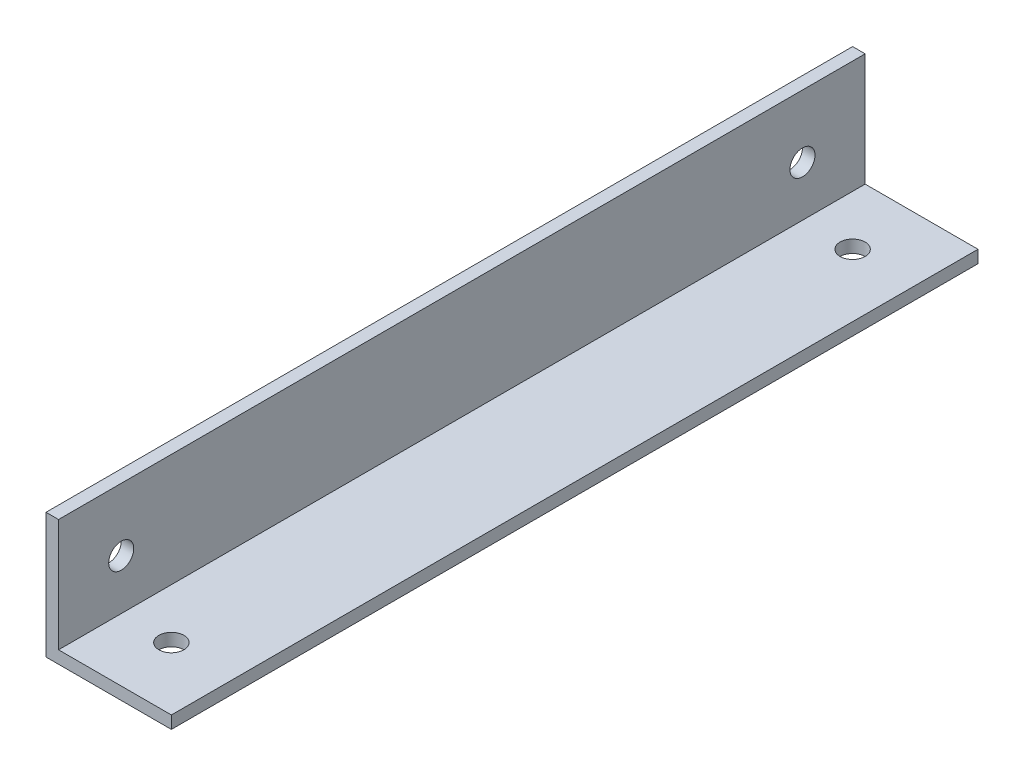
SolidWorks part; units mm, degrees
ref_plane "Plan de face" through (0, 0, 0) normal (0, 0, 1) x (1, 0, 0)
ref_plane "Plan de dessus" through (0, 0, 0) normal (0, 1, 0) x (1, 0, 0)
ref_plane "Plan de droite" through (0, 0, 0) normal (1, 0, 0) x (0, 0, -1)
sketch "Esquisse1" plane through (0, 0, 0) normal (0, 0, 1) x (1, 0, 0)
  line L0 (-19.573, -1.5638) -> (-19.573, -16.5638)
  line L1 (-19.573, -16.5638) -> (-4.573, -16.5638)
  line L2 (-4.573, -16.5638) -> (-4.573, -15.0638)
  line L3 (-4.573, -15.0638) -> (-18.073, -15.0638)
  line L4 (-18.073, -15.0638) -> (-18.073, -1.5638)
  line L5 (-18.073, -1.5638) -> (-19.573, -1.5638)
  dimension "D1" = 1.5
  dimension "D2" = 1.5
  dimension "D3" = 15
  dimension "D4" = 15
extrude "Extrusion1" add sketch "Esquisse1" along normal blind 96.5
sketch "Esquisse2" plane through (0, -16.5638, 0) normal (0, -1, 0) x (1, 0, 0)
  line L0 (-12.073, 89) -> (-12.073, 7.5) construction
  line L1 (-4.573, 96.5) -> (-4.573, 0) construction
  line L2 (-19.573, 0) -> (-4.573, 0) construction
  line L3 (-19.573, 96.5) -> (-4.573, 96.5) construction
  circle A0 centre (-12.073, 89) radius 1.5
  circle A1 centre (-12.073, 7.5) radius 1.5
  dimension "D1" = 7.5
  dimension "D2" = 7.5
  dimension "D3" = 7.5
extrude "Extrusion2" cut sketch "Esquisse2" against normal blind 98
sketch "Esquisse3" plane through (-19.573, 0, 0) normal (-1, 0, 0) x (0, 0, 1)
  line L0 (89, -9.0638) -> (7.5, -9.0638) construction
  line L1 (96.5, -1.5638) -> (0, -1.5638) construction
  line L2 (96.5, -1.5638) -> (96.5, -16.5638) construction
  line L3 (0, -1.5638) -> (0, -16.5638) construction
  circle A0 centre (89, -9.0638) radius 1.5
  circle A1 centre (7.5, -9.0638) radius 1.5
  dimension "D1" = 7.5
  dimension "D2" = 7.5
  dimension "D3" = 7.5
extrude "Extrusion3" cut sketch "Esquisse3" against normal blind 98
